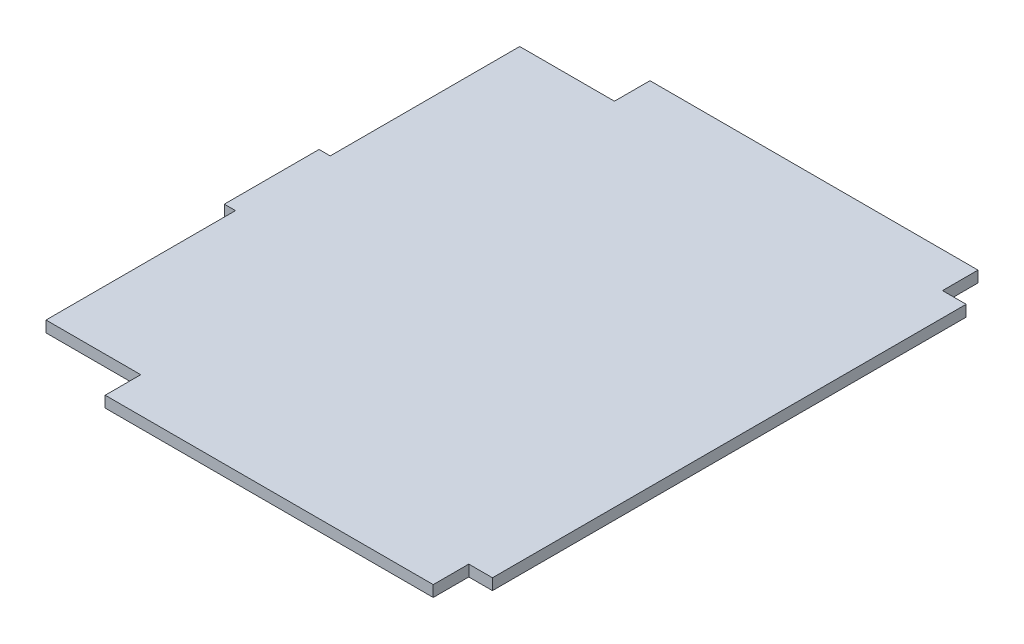
SolidWorks part; units mm, degrees
material "Acrylic (Medium-high impact)"
ref_plane "Front Plane" through (0, 0, 0) normal (0, 0, 1) x (1, 0, 0)
ref_plane "Top Plane" through (0, 0, 0) normal (0, 1, 0) x (1, 0, 0)
ref_plane "Right Plane" through (0, 0, 0) normal (1, 0, 0) x (0, 0, -1)
sketch "Sketch1" plane through (0, 0, 0) normal (0, 1, 0) x (1, 0, 0)
  line L0 (-59.8473, 66.4972) -> (59.8473, 66.4972) construction
  line L1 (59.8473, -73.025) -> (-59.8473, -73.025)
  line L2 (59.8473, -73.025) -> (59.8473, 73.025)
  line L3 (59.8473, 73.025) -> (-59.8473, 73.025)
  line L4 (-59.8473, -73.025) -> (-59.8473, 73.025)
  line L5 (59.8473, -73.025) -> (-59.8473, 73.025) construction
  line L6 (59.8473, 73.025) -> (-59.8473, -73.025) construction
  line L7 (-59.8473, -66.4972) -> (59.8473, -66.4972) construction
  line L8 (-59.8473, 66.4972) -> (-59.8473, -66.4972) construction
  line L9 (59.8473, 66.4972) -> (59.8473, -66.4972) construction
  line L19 (-59.8473, -12.7) -> (-62.8445, -12.7)
  line L20 (-59.8473, -73.025) -> (-34.4473, -73.025)
  line L21 (-59.8473, -73.025) -> (-59.8473, -63.5)
  line L22 (-59.8473, -63.5) -> (-34.4473, -63.5)
  line L23 (-34.4473, -73.025) -> (-34.4473, -63.5)
  line L24 (-59.8473, 73.025) -> (-34.4473, 73.025)
  line L25 (-59.8473, 73.025) -> (-59.8473, 63.5)
  line L26 (-59.8473, 63.5) -> (-34.4473, 63.5)
  line L27 (-34.4473, 73.025) -> (-34.4473, 63.5)
  line L28 (-59.8473, -12.7) -> (-59.8473, 12.7)
  line L29 (-59.8473, 12.7) -> (-62.8445, 12.7)
  line L30 (-62.8445, -12.7) -> (-62.8445, 12.7)
  line L31 (59.8473, 73.025) -> (53.4973, 73.025)
  line L32 (59.8473, 73.025) -> (59.8473, 63.5)
  line L33 (59.8473, 63.5) -> (53.4973, 63.5)
  line L34 (53.4973, 73.025) -> (53.4973, 63.5)
  line L35 (59.8473, -73.025) -> (53.4973, -73.025)
  line L36 (59.8473, -73.025) -> (59.8473, -63.5)
  line L37 (59.8473, -63.5) -> (53.4973, -63.5)
  line L38 (53.4973, -73.025) -> (53.4973, -63.5)
  point P0 (0, 0)
  point P10 (59.8473, 0)
  point P11 (59.8473, 0)
  point P16 (-62.8445, 0)
  dimension "D1" = 119.6947
  dimension "D2" = 146.05
  dimension "D3" = 132.9944
  dimension "D4" = 127
  dimension "D5" = 25.4
  dimension "D6" = 25.4
  dimension "D7" = 2.9972
  dimension "D8" = 6.35
extrude "Boss-Extrude1" add sketch "Sketch1" along normal blind 2.9972 contours L3 L27 L26 L4 L22 L23 L1 L2 | L30 L19 L4 L29
